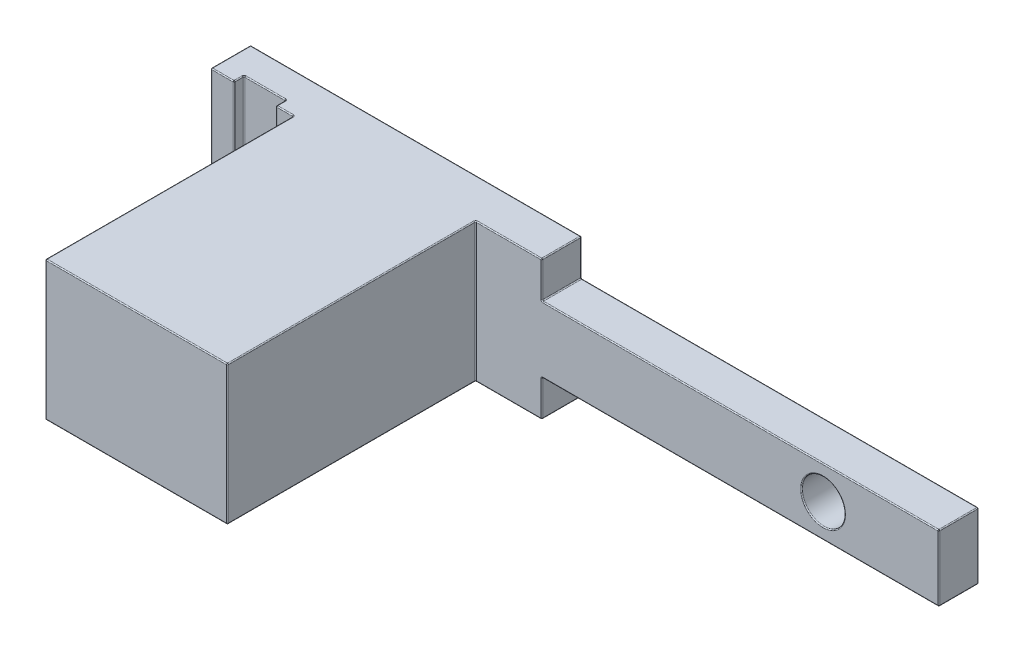
SolidWorks part; units mm, degrees
ref_plane "Front Plane" through (0, 0, 0) normal (0, 0, 1) x (1, 0, 0)
ref_plane "Top Plane" through (0, 0, 0) normal (0, 1, 0) x (1, 0, 0)
ref_plane "Right Plane" through (0, 0, 0) normal (1, 0, 0) x (0, 0, -1)
sketch "Sketch1" plane through (0, 0, 0) normal (0, 0, 1) x (1, 0, 0)
  line L1 (25.4, 10.668) -> (0, 10.668)
  line L2 (25.4, 10.668) -> (25.4, 0)
  line L3 (25.4, 0) -> (0, 0)
  line L4 (0, 10.668) -> (0, 0)
  line L5 (25.4, 7.874) -> (55.88, 7.874)
  line L6 (25.4, 7.874) -> (25.4, 2.794)
  line L7 (25.4, 2.794) -> (55.88, 2.794)
  line L8 (55.88, 7.874) -> (55.88, 2.794)
  circle A0 centre (46.99, 5.334) radius 1.651
  dimension "D6" = 3.302
  dimension "D1" = 25.4
  dimension "D2" = 10.668
  dimension "D3" = 5.08
  dimension "D4" = 2.794
  dimension "D5" = 30.48
  dimension "D7" = 2.54
  dimension "D8" = 8.89
extrude "Boss-Extrude1" add sketch "Sketch1" along normal blind 3.048 contours L8 L5 L2 L7 A0 | L1 L4 L3 L2
sketch "Sketch2" plane through (0, 0, 3.048) normal (0, 0, 1) x (1, 0, 0)
  line L0 (25.4, 10.668) -> (0, 10.668) construction
  line L1 (6.35, 10.668) -> (20.32, 10.668)
  line L2 (6.35, 10.668) -> (6.35, 0)
  line L3 (6.35, 0) -> (20.32, 0)
  line L4 (20.32, 10.668) -> (20.32, 0)
  line L5 (25.4, 0) -> (0, 0) construction
  line L6 (0, 10.668) -> (0, 0) construction
  line L7 (25.4, 10.668) -> (25.4, 7.874) construction
  dimension "D1" = 6.35
  dimension "D2" = 5.08
extrude "Boss-Extrude2" add sketch "Sketch2" along normal blind 19.05
sketch "Sketch3" plane through (0, 0, 3.048) normal (0, 0, 1) x (1, 0, 0)
  line L0 (6.35, 10.668) -> (0, 10.668) construction
  line L1 (1.778, 10.668) -> (4.9961, 10.668)
  line L2 (1.778, 10.668) -> (1.778, 0)
  line L3 (1.778, 0) -> (4.9961, 0)
  line L4 (4.9961, 10.668) -> (4.9961, 0)
  line L5 (6.35, 0) -> (0, 0) construction
  line L6 (0, 10.668) -> (0, 0) construction
  dimension "D1" = 3.2181
  dimension "D2" = 1.778
extrude "Cut-Extrude1" cut sketch "Sketch3" against normal blind 0.762
fillet "Fillet1" radius 0.075 50 edges at (0, 5.334, 3.048) (1.778, 5.334, 3.048) (4.9961, 5.334, 3.048) (4.9961, 5.334, 2.286) (1.778, 5.334, 2.286) (25.4, 7.874, 1.524) (55.88, 7.874, 1.524) (40.64, 7.874, 0) (25.4, 9.271, 0) (0, 5.334, 0) (25.4, 1.397, 0) (55.88, 5.334, 0) (48.641, 5.334, 0) (25.4, 2.794, 1.524) (55.88, 2.794, 1.524) (40.64, 2.794, 0) (3.387, 0, 2.286) (4.9961, 0, 2.667) (5.673, 0, 3.048) (25.4, 0, 1.524) (12.7, 0, 0) (0, 0, 1.524) (0.889, 0, 3.048) (1.778, 0, 2.667) (48.641, 5.334, 3.048) (25.4, 9.271, 3.048) (40.64, 7.874, 3.048) (55.88, 5.334, 3.048) (40.64, 2.794, 3.048) (25.4, 1.397, 3.048) (22.86, 0, 3.048) (20.32, 0, 12.573) (20.32, 5.334, 3.048) (0, 10.668, 1.524) (12.7, 10.668, 0) (25.4, 10.668, 1.524) (22.86, 10.668, 3.048) (20.32, 10.668, 12.573) (5.673, 10.668, 3.048) (4.9961, 10.668, 2.667) (3.387, 10.668, 2.286) (1.778, 10.668, 2.667) (0.889, 10.668, 3.048) (6.35, 10.668, 12.573) (6.35, 0, 12.573) (6.35, 5.334, 3.048) (13.335, 10.668, 22.098) (20.32, 5.334, 22.098) (13.335, 0, 22.098) (6.35, 5.334, 22.098)
